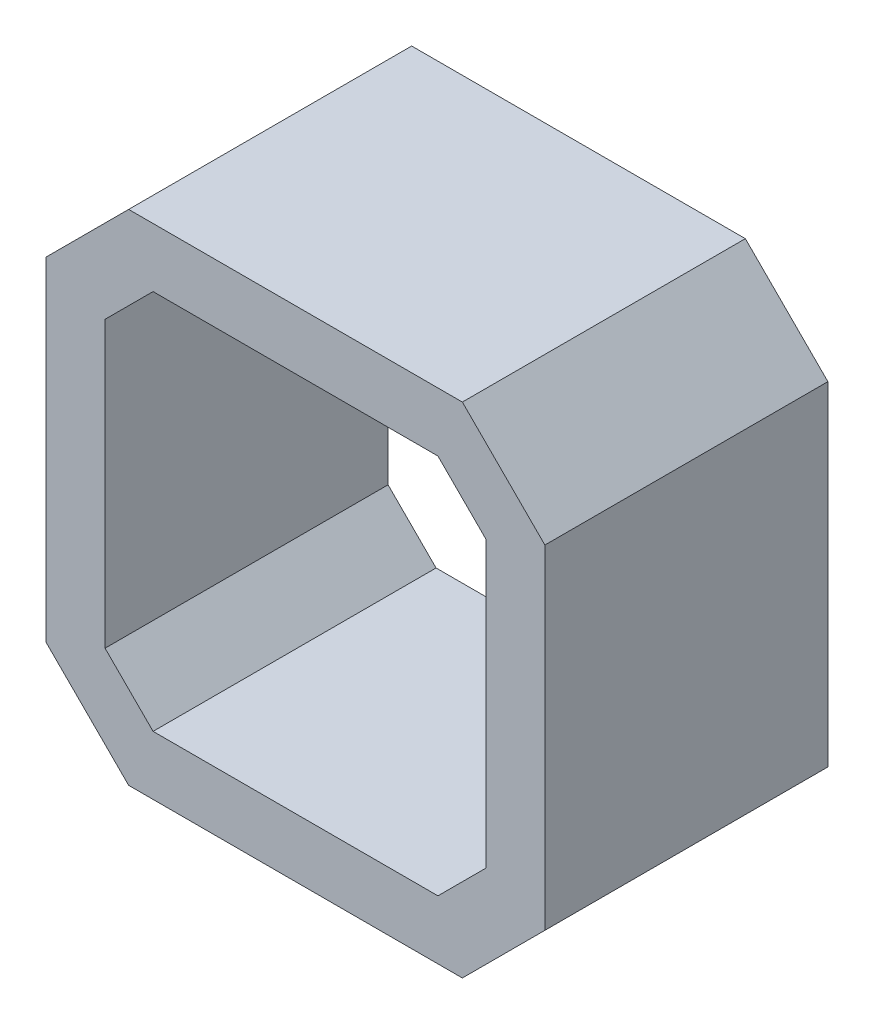
SolidWorks part; units mm, degrees
ref_plane "Front Plane" through (0, 0, 0) normal (0, 0, 1) x (1, 0, 0)
ref_plane "Top Plane" through (0, 0, 0) normal (0, 1, 0) x (1, 0, 0)
ref_plane "Right Plane" through (0, 0, 0) normal (1, 0, 0) x (0, 0, -1)
sketch "Sketch1" plane through (0, 0, 0) normal (0, 0, 1) x (1, 0, 0)
  line L0 (-14.15, 21.15) -> (-21.15, 14.15)
  line L1 (14.15, -21.15) -> (-14.15, -21.15)
  line L2 (21.15, -14.15) -> (21.15, 14.15)
  line L3 (14.15, 21.15) -> (-14.15, 21.15)
  line L4 (-21.15, -14.15) -> (-21.15, 14.15)
  line L5 (21.15, -21.15) -> (-21.15, 21.15) construction
  line L6 (21.15, 21.15) -> (-21.15, -21.15) construction
  line L7 (21.15, 14.15) -> (14.15, 21.15)
  line L8 (21.15, -14.15) -> (14.15, -21.15)
  line L9 (-14.15, -21.15) -> (-21.15, -14.15)
  line L10 (12.0789, 16.15) -> (-12.0789, 16.15)
  line L11 (-12.0789, 16.15) -> (-16.15, 12.0789)
  line L12 (-16.15, -12.0789) -> (-16.15, 12.0789)
  line L13 (-12.0789, -16.15) -> (-16.15, -12.0789)
  line L14 (12.0789, -16.15) -> (-12.0789, -16.15)
  line L15 (16.15, -12.0789) -> (12.0789, -16.15)
  line L16 (16.15, -12.0789) -> (16.15, 12.0789)
  line L17 (16.15, 12.0789) -> (12.0789, 16.15)
  point P0 (0, 0)
  dimension "D1" = 42.3
  dimension "D2" = 5
extrude "Boss-Extrude1" add sketch "Sketch1" along normal blind 24
